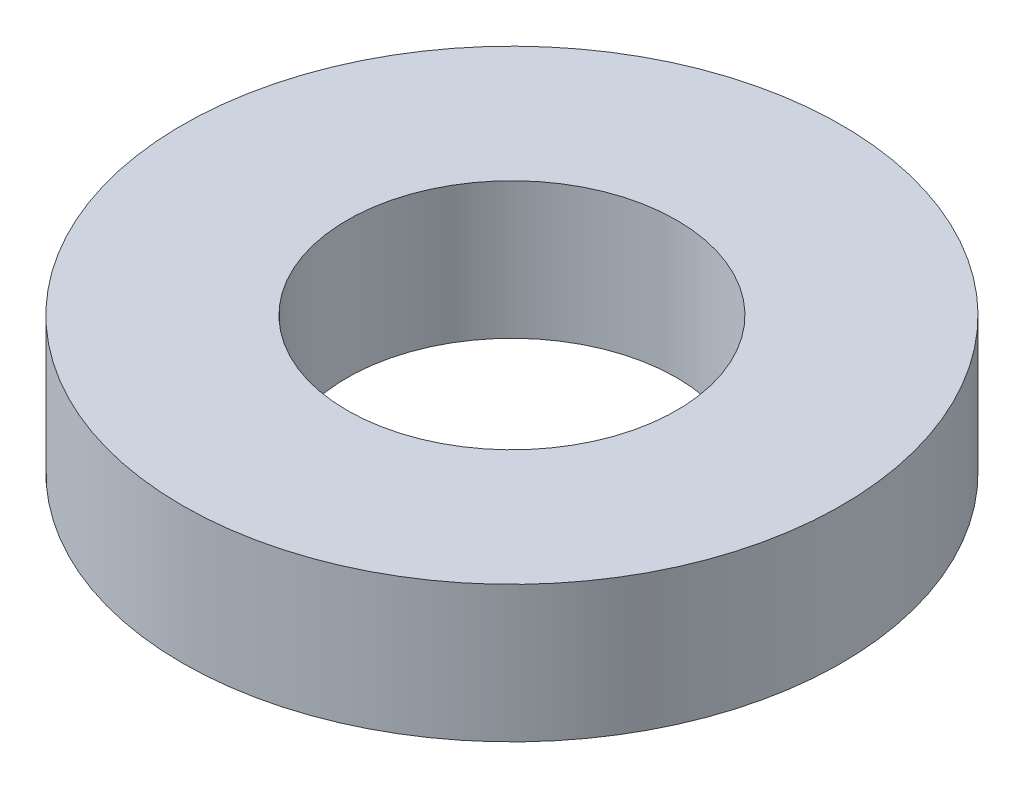
SolidWorks part; units mm, degrees
material "1.4511 (X3CrNb17)"
ref_plane "前视基准面" through (0, 0, 0) normal (0, 0, 1) x (1, 0, 0)
ref_plane "上视基准面" through (0, 0, 0) normal (0, 1, 0) x (1, 0, 0)
ref_plane "右视基准面" through (0, 0, 0) normal (1, 0, 0) x (0, 0, -1)
sketch "草图1" plane through (0, 0, 0) normal (0, 1, 0) x (1, 0, 0)
  circle A0 centre (0, 0) radius 5
  dimension "D1" = 10
extrude "凸台-拉伸1" add sketch "草图1" along normal blind 2.07
sketch "草图2" plane through (0, 2.07, 0) normal (0, 1, 0) x (1, 0, 0)
  circle A0 centre (0, 0) radius 2.5
  dimension "D1" = 5
extrude "切除-拉伸1" cut sketch "草图2" against normal through all
